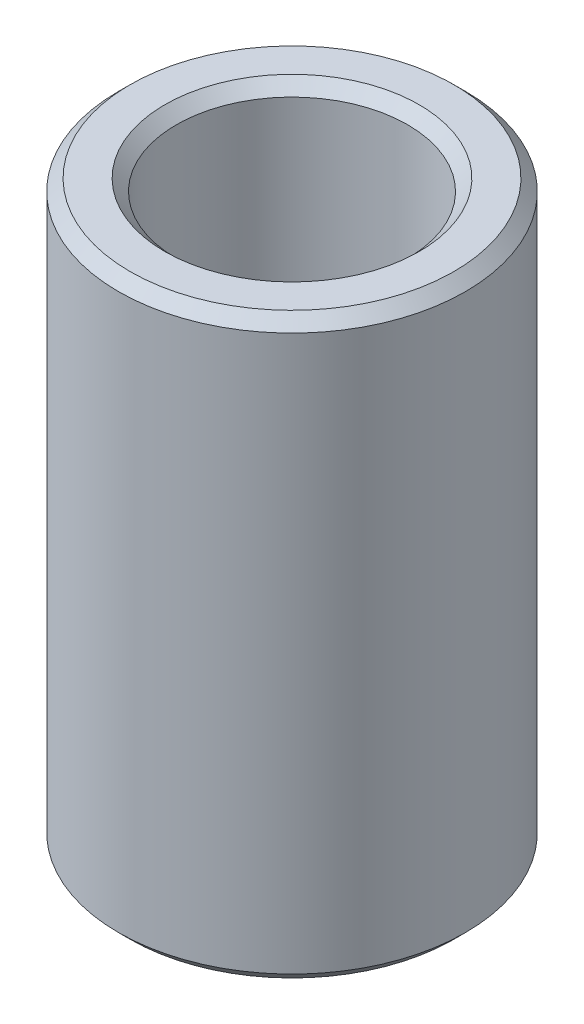
SolidWorks part; units mm, degrees
ref_plane "Front Plane" through (0, 0, 0) normal (0, 0, 1) x (1, 0, 0)
ref_plane "Top Plane" through (0, 0, 0) normal (0, 1, 0) x (1, 0, 0)
ref_plane "Right Plane" through (0, 0, 0) normal (1, 0, 0) x (0, 0, -1)
sketch "Sketch1" plane through (0, 0, 0) normal (0, 1, 0) x (1, 0, 0)
  circle A0 centre (0, 0) radius 2
  circle A1 centre (0, 0) radius 3
extrude "Boss-Extrude1" add sketch "Sketch1" along normal blind 10
chamfer "Chamfer1" distance 0.2 angle 45 3 edges at (0, 0, 3) (0, 10, 2) (0, 10, 3)
